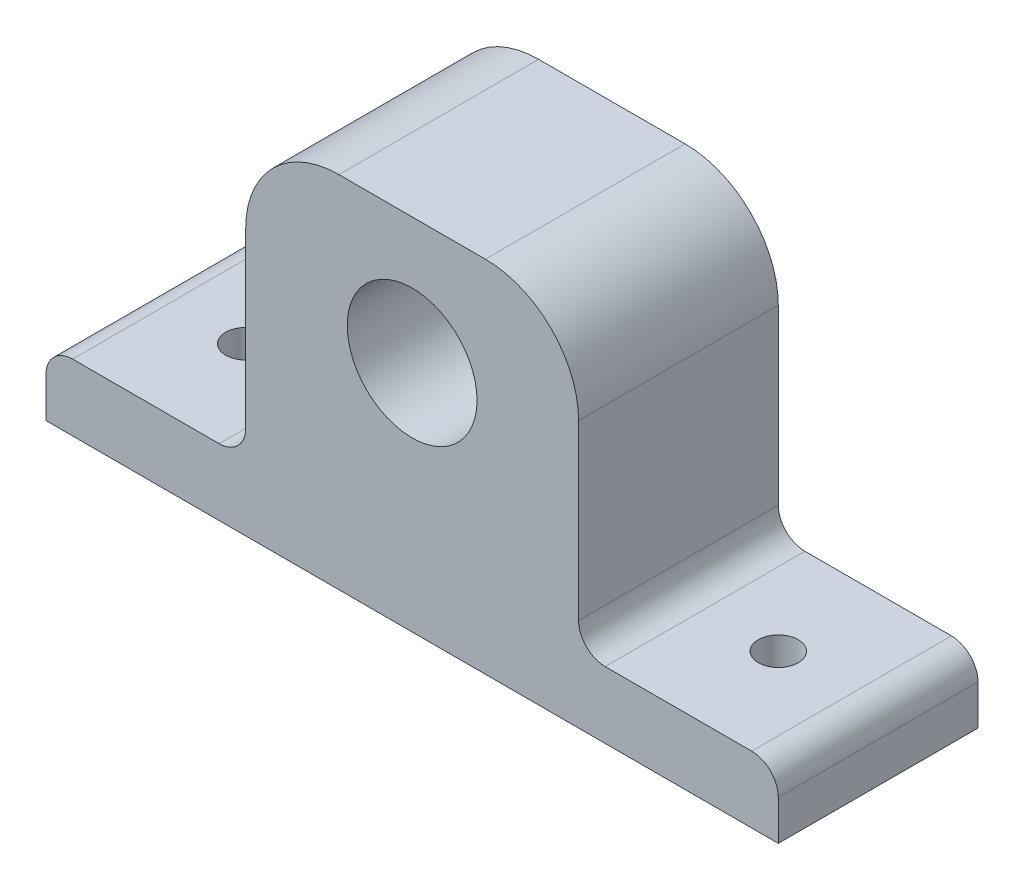
SolidWorks part; units mm, degrees
ref_plane "Front Plane" through (0, 0, 0) normal (0, 0, 1) x (1, 0, 0)
ref_plane "Top Plane" through (0, 0, 0) normal (0, 1, 0) x (1, 0, 0)
ref_plane "Right Plane" through (0, 0, 0) normal (1, 0, 0) x (0, 0, -1)
sketch "Sketch1" plane through (0, 0, 0) normal (0, 1, 0) x (1, 0, 0)
  line L1 (-27.5, -7.5) -> (27.5, -7.5)
  line L2 (-27.5, -7.5) -> (-27.5, 7.5)
  line L3 (-27.5, 7.5) -> (27.5, 7.5)
  line L4 (27.5, -7.5) -> (27.5, 7.5)
  line L5 (-27.5, -7.5) -> (27.5, 7.5) construction
  line L6 (-27.5, 7.5) -> (27.5, -7.5) construction
  point P0 (0, 0)
  dimension "D1" = 55
  dimension "D2" = 15
extrude "Boss-Extrude1" add sketch "Sketch1" along normal blind 27
sketch "Sketch2" plane through (0, 0, 7.5) normal (0, 0, 1) x (1, 0, 0)
  line L0 (0, 0) -> (0, 27) construction
  line L1 (-27.5, 27) -> (27.5, 27) construction
  circle A0 centre (0, 17.5) radius 4.875
  dimension "D1" = 9.75
  dimension "D2" = 17.5
extrude "Cut-Extrude1" cut sketch "Sketch2" against normal through all both
sketch "Sketch4" plane through (0, 27, 0) normal (0, 1, 0) x (1, 0, 0)
  line L0 (-27.5, -7.5) -> (27.5, -7.5) construction
  line L3 (-27.5, 7.5) -> (-12.5, 7.5)
  line L4 (-27.5, 7.5) -> (-27.5, -7.5)
  line L5 (-27.5, -7.5) -> (-12.5, -7.5)
  line L6 (-12.5, 7.5) -> (-12.5, -7.5)
  line L8 (27.5, 7.5) -> (12.5, 7.5)
  line L9 (27.5, 7.5) -> (27.5, -7.5)
  line L10 (27.5, -7.5) -> (12.5, -7.5)
  line L11 (12.5, 7.5) -> (12.5, -7.5)
  dimension "D1" = 15
extrude "Cut-Extrude2" cut sketch "Sketch4" against normal blind 22
sketch "Sketch5" plane through (0, 5, 0) normal (0, 1, 0) x (1, 0, 0)
  line L0 (-27.5, 7.5) -> (-12.5, -7.5) construction
  line L1 (12.5, -7.5) -> (27.5, 7.5) construction
  circle A0 centre (-20, 0) radius 1.5
  circle A1 centre (20, 0) radius 1.5
  dimension "D1" = 3
  dimension "D2" = 3
extrude "Cut-Extrude3" cut sketch "Sketch5" against normal through all both and the other way through all
fillet "Fillet1" radius 2 4 edges at (12.5, 5, 0) (-12.5, 5, 0) (27.5, 5, 0) (-27.5, 5, 0)
fillet "Fillet2" radius 7 2 edges at (-12.5, 27, 0) (12.5, 27, 0)
